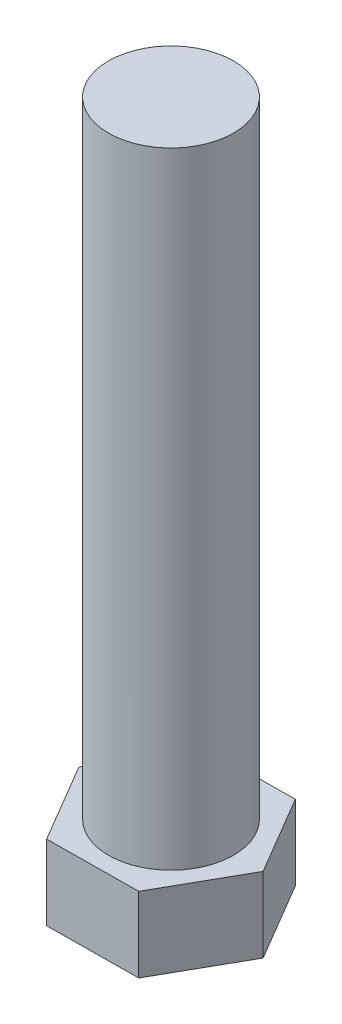
SolidWorks part; units mm, degrees
ref_plane "Спереди" through (0, 0, 0) normal (0, 0, 1) x (1, 0, 0)
ref_plane "Сверху" through (0, 0, 0) normal (0, 1, 0) x (1, 0, 0)
ref_plane "Справа" through (0, 0, 0) normal (1, 0, 0) x (0, 0, -1)
sketch "Эскиз1" plane through (0, 0, 0) normal (0, 1, 0) x (1, 0, 0)
  circle A0 centre (0, 0) radius 5
  dimension "D1" = 10
extrude "Бобышка-Вытянуть1" add sketch "Эскиз1" along normal blind 50
sketch "Эскиз2" plane through (0, 0, 0) normal (0, -1, 0) x (1, 0, 0)
  line L1 (3.7062, 6.2851) -> (-3.5899, 6.3522)
  line L2 (-3.5899, 6.3522) -> (-7.2961, 0.0672)
  line L3 (-7.2961, 0.0672) -> (-3.7062, -6.2851)
  line L4 (-3.7062, -6.2851) -> (3.5899, -6.3522)
  line L5 (3.5899, -6.3522) -> (7.2961, -0.0672)
  line L6 (7.2961, -0.0672) -> (3.7062, 6.2851)
  circle A0 centre (0, 0) radius 6.3189 construction
extrude "Бобышка-Вытянуть2" add sketch "Эскиз2" along normal blind 6
